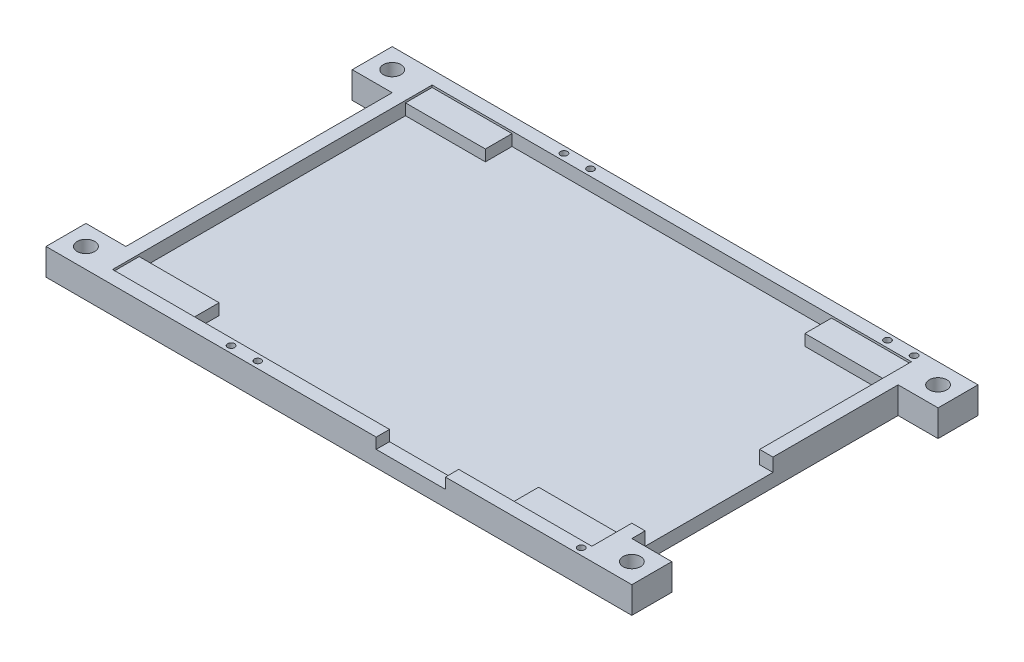
SolidWorks part; units mm, degrees
ref_plane "Front Plane" through (0, 0, 0) normal (0, 0, 1) x (1, 0, 0)
ref_plane "Top Plane" through (0, 0, 0) normal (0, 1, 0) x (1, 0, 0)
ref_plane "Right Plane" through (0, 0, 0) normal (1, 0, 0) x (0, 0, -1)
sketch "Sketch1" plane through (0, 0, 0) normal (0, 1, 0) x (1, 0, 0)
  line L1 (0, 0) -> (95, 0)
  line L2 (0, 0) -> (0, 65)
  line L3 (0, 65) -> (95, 65)
  line L4 (95, 0) -> (95, 65)
  dimension "D1" = 65
  dimension "D2" = 95
sketch "Sketch3" plane through (0, 0, 0) normal (0, 1, 0) x (1, 0, 0)
  line L1 (2.5, 2.5) -> (92.5, 2.5)
  line L2 (2.5, 2.5) -> (2.5, 62.5)
  line L3 (2.5, 62.5) -> (92.5, 62.5)
  line L4 (92.5, 2.5) -> (92.5, 62.5)
  dimension "D1" = 2.5
  dimension "D2" = 2.5
  dimension "D3" = 60
  dimension "D4" = 90
extrude "Boss-Extrude1" add sketch "Sketch1" against normal blind 5
extrude "Cut-Extrude1" cut sketch "Sketch3" against normal blind 2.5
sketch "Sketch5" plane through (0, -2.5, 0) normal (0, 1, 0) x (1, 0, 0)
  line L1 (2.5, 62.5) -> (17.5, 62.5)
  line L2 (2.5, 62.5) -> (2.5, 57.5)
  line L3 (2.5, 57.5) -> (17.5, 57.5)
  line L4 (17.5, 62.5) -> (17.5, 57.5)
  line L5 (2.5, 2.5) -> (17.5, 2.5)
  line L6 (2.5, 2.5) -> (2.5, 7.5)
  line L7 (2.5, 7.5) -> (17.5, 7.5)
  line L8 (17.5, 2.5) -> (17.5, 7.5)
  line L9 (92.5, 62.5) -> (77.5, 62.5)
  line L10 (92.5, 62.5) -> (92.5, 57.5)
  line L11 (92.5, 57.5) -> (77.5, 57.5)
  line L12 (77.5, 62.5) -> (77.5, 57.5)
  line L13 (92.5, 2.5) -> (77.5, 2.5)
  line L14 (92.5, 2.5) -> (92.5, 7.5)
  line L15 (92.5, 7.5) -> (77.5, 7.5)
  line L16 (77.5, 2.5) -> (77.5, 7.5)
  dimension "D1" = 5
  dimension "D2" = 15
extrude "Boss-Extrude2" add sketch "Sketch5" along normal blind 2.1
sketch "Sketch14" plane through (0, 0, 0) normal (0, 0, 1) x (1, 0, 0)
  line L0 (0, 0) -> (95, 0) construction
  line L1 (67.5, 0) -> (54.5, 0)
  line L2 (67.5, 0) -> (67.5, -2)
  line L3 (67.5, -2) -> (54.5, -2)
  line L4 (54.5, 0) -> (54.5, -2)
  line L5 (0, -5) -> (0, 0) construction
  point P8 (61, -2)
  dimension "D1" = 61
  dimension "D2" = 13
  dimension "D3" = 2
extrude "Cut-Extrude3" cut sketch "Sketch14" against normal up to surface (2.5 mm away) up to face at (47.5, -0.825, -2.5)
sketch "Sketch15" plane through (0, 0, 0) normal (0, 1, 0) x (1, 0, 0)
sketch "Sketch17" plane through (95, 0, 0) normal (1, 0, 0) x (0, 0, -1)
  line L1 (10, -2.5) -> (34, -2.5)
  line L2 (10, -2.5) -> (10, 0)
  line L3 (10, 0) -> (34, 0)
  line L4 (34, -2.5) -> (34, 0)
  line L5 (0, -5) -> (0, 0) construction
  line L6 (65, -5) -> (65, 0) construction
  line L7 (0, 0) -> (65, 0) construction
  point P10 (0, 0)
  dimension "D1" = 10
  dimension "D2" = 31
  dimension "D3" = 2.5
extrude "Cut-Extrude5" cut sketch "Sketch17" against normal up to next
sketch "Sketch18" plane through (0, 0, 0) normal (0, 1, 0) x (1, 0, 0)
  line L0 (58.875, 65) -> (58.875, 0) construction
  line L1 (95, 65) -> (0, 65) construction
  line L2 (0, 0) -> (54.5, 0) construction
  line L3 (95, 34) -> (95, 65) construction
  line L4 (92.5, 62.5) -> (77.5, 62.5) construction
  line L5 (92.5, 62.5) -> (2.5, 62.5) construction
  line L6 (0, 32.5) -> (95, 32.5) construction
  line L7 (0, 65) -> (0, 0) construction
  line L8 (95, 10) -> (95, 34) construction
  circle A0 centre (91.75, 63.75) radius 0.65
  circle A1 centre (86.75, 63.75) radius 0.65
  circle A3 centre (91.75, 1.25) radius 0.65
  circle A4 centre (26, 63.75) radius 0.65
  circle A5 centre (31, 63.75) radius 0.65
  circle A6 centre (26, 1.25) radius 0.65
  circle A7 centre (31, 1.25) radius 0.65
  dimension "D2" = 1.3
  dimension "D6" = 1.3
  dimension "D1" = 36.125
  dimension "D3" = 1.25
  dimension "D4" = 0.75
  dimension "D5" = 1.25
  dimension "D7" = 5
extrude "Cut-Extrude6" cut sketch "Sketch18" against normal blind 2.5
sketch "Sketch19" plane through (0, 0, 0) normal (-1, 0, 0) x (0, 0, 1)
  line L0 (-65, -5) -> (0, -5) construction
  line L1 (-65, 0) -> (-57.5, 0)
  line L2 (-65, 0) -> (-65, -5)
  line L3 (-65, -5) -> (-57.5, -5)
  line L4 (-57.5, 0) -> (-57.5, -5)
  line L6 (0, 0) -> (-7.5, 0)
  line L7 (0, 0) -> (0, -5)
  line L8 (0, -5) -> (-7.5, -5)
  line L9 (-7.5, 0) -> (-7.5, -5)
  dimension "D1" = 7.5
  dimension "D2" = 7.5
extrude "Boss-Extrude3" add sketch "Sketch19" along normal blind 7.5
sketch "Sketch20" plane through (95, 0, 0) normal (1, 0, 0) x (0, 0, -1)
  line L4 (7.5, 0) -> (0, 0)
  line L5 (7.5, -5) -> (7.5, 0)
  line L6 (0, -5) -> (7.5, -5)
  line L7 (0, 0) -> (0, -5)
  line L8 (7.5, 0) -> (0, 0)
  line L9 (7.5, -5) -> (7.5, 0)
  line L10 (0, -5) -> (7.5, -5)
  line L11 (0, 0) -> (0, -5)
  line L12 (65, 0) -> (57.5, 0)
  line L13 (57.5, 0) -> (57.5, -5)
  line L14 (57.5, -5) -> (65, -5)
  line L15 (65, -5) -> (65, 0)
  line L16 (65, 0) -> (57.5, 0)
  line L17 (57.5, 0) -> (57.5, -5)
  line L18 (57.5, -5) -> (65, -5)
  line L19 (65, -5) -> (65, 0)
  dimension "D1" = 0
  dimension "D2" = 0
extrude "Boss-Extrude4" add sketch "Sketch20" along normal blind 7.5
sketch "Sketch21" plane through (0, 0, 0) normal (0, 1, 0) x (1, 0, 0)
  line L0 (-7.5, 57.5) -> (-7.5, 65) construction
  line L1 (-7.5, 57.5) -> (0, 57.5) construction
  line L2 (47.5, 65) -> (47.5, 0) construction
  line L3 (102.5, 65) -> (-7.5, 65) construction
  line L4 (-7.5, 0) -> (54.5, 0) construction
  line L5 (0, 32.5) -> (95, 32.5) construction
  line L6 (0, 57.5) -> (0, 7.5) construction
  line L7 (95, 10) -> (95, 34) construction
  circle A0 centre (-3.75, 61.25) radius 1.65
  circle A1 centre (98.75, 61.25) radius 1.65
  circle A2 centre (98.75, 3.75) radius 1.65
  circle A3 centre (-3.75, 3.75) radius 1.65
  dimension "D1" = 3.3
  dimension "D2" = 3.75
  dimension "D3" = 3.75
extrude "Cut-Extrude7" cut sketch "Sketch21" against normal through all
